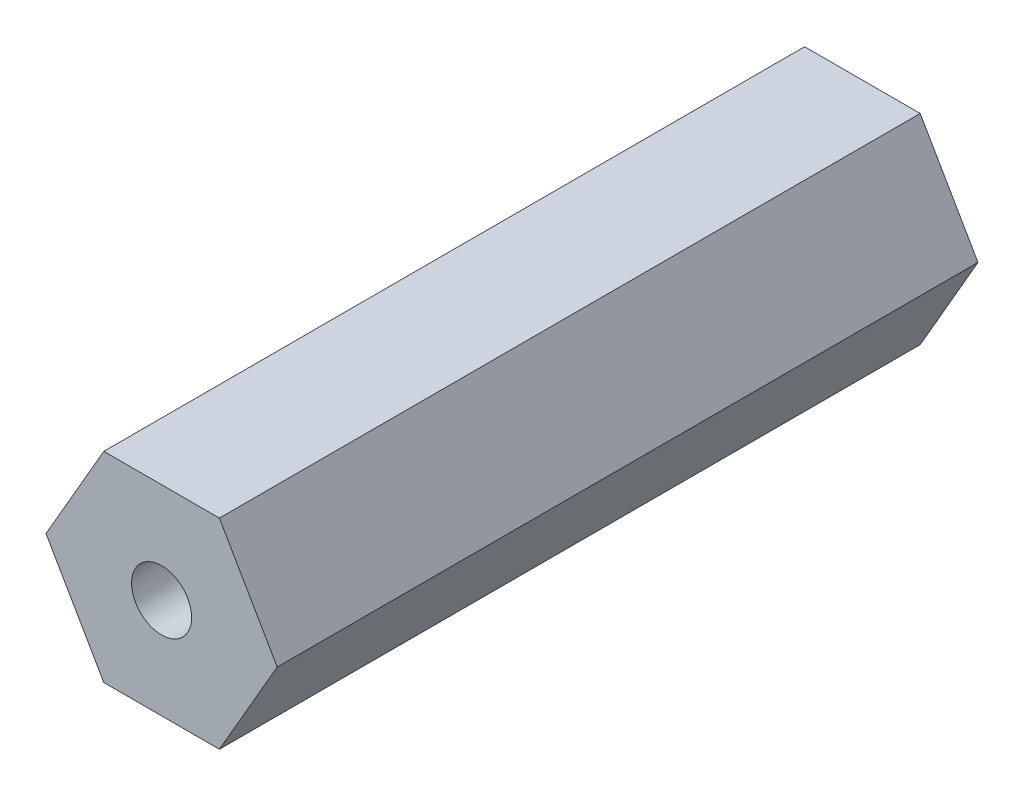
SolidWorks part; units mm, degrees
ref_plane "Front Plane" through (0, 0, 0) normal (0, 0, 1) x (1, 0, 0)
ref_plane "Top Plane" through (0, 0, 0) normal (0, 1, 0) x (1, 0, 0)
ref_plane "Right Plane" through (0, 0, 0) normal (1, 0, 0) x (0, 0, -1)
sketch "Sketch1" plane through (0, 0, 0) normal (0, 0, 1) x (1, 0, 0)
  line L1 (5.7735, 0) -> (2.8868, 5)
  line L2 (2.8868, 5) -> (-2.8868, 5)
  line L3 (-2.8868, 5) -> (-5.7735, 0)
  line L4 (-5.7735, 0) -> (-2.8868, -5)
  line L5 (-2.8868, -5) -> (2.8868, -5)
  line L6 (2.8868, -5) -> (5.7735, 0)
  circle A0 centre (0, 0) radius 5 construction
  circle A1 centre (0, 0) radius 1.5
extrude "Boss-Extrude1" add sketch "Sketch1" along normal blind 35
